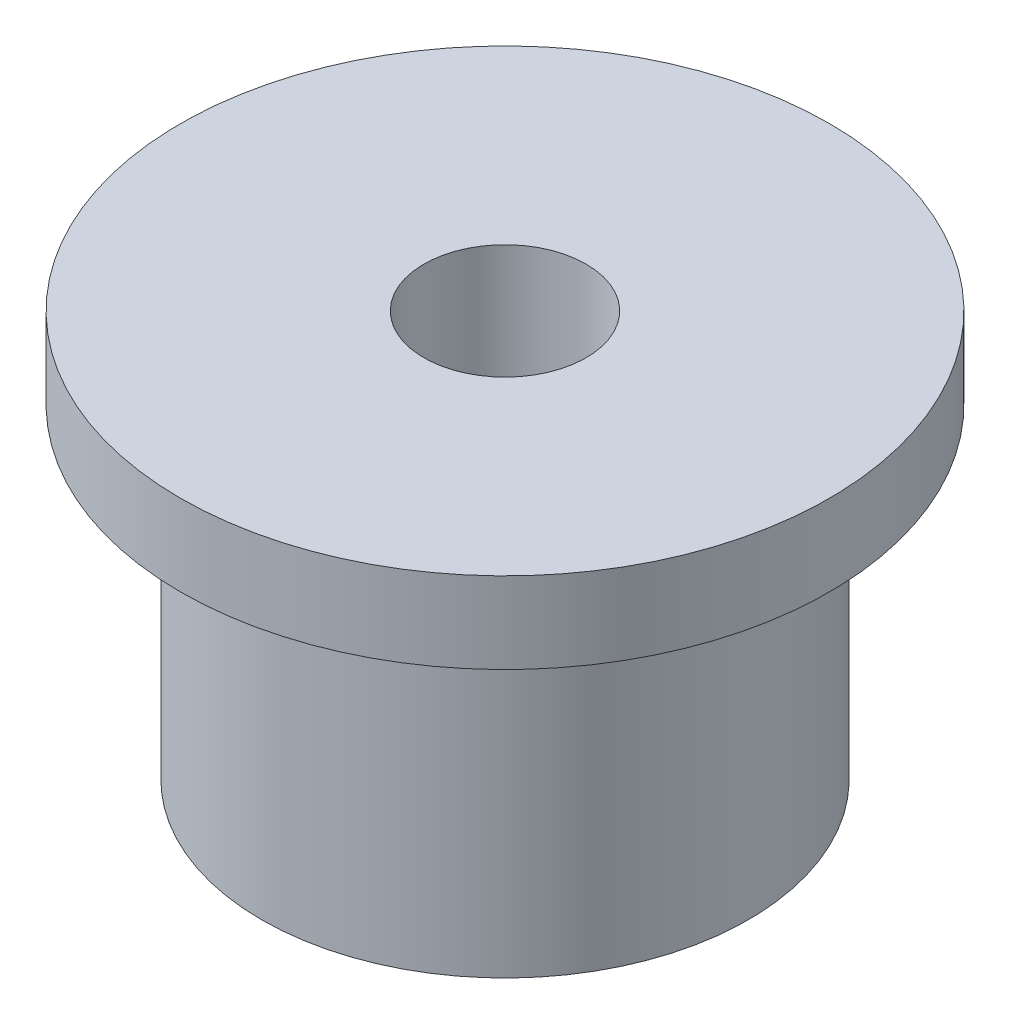
SolidWorks part; units mm, degrees
ref_plane "Front Plane" through (0, 0, 0) normal (0, 0, 1) x (1, 0, 0)
ref_plane "Top Plane" through (0, 0, 0) normal (0, 1, 0) x (1, 0, 0)
ref_plane "Right Plane" through (0, 0, 0) normal (1, 0, 0) x (0, 0, -1)
sketch "Sketch1" plane through (0, 0, 0) normal (0, 1, 0) x (1, 0, 0)
  circle A0 centre (0, 0) radius 100
  dimension "D1" = 200
extrude "Boss-Extrude1" add sketch "Sketch1" along normal blind 25
sketch "Sketch3" plane through (0, 0, 0) normal (0, -1, 0) x (1, 0, 0)
  circle A0 centre (0, 0) radius 75
  dimension "D1" = 150
extrude "Boss-Extrude2" add sketch "Sketch3" along normal blind 100
sketch "Sketch4" plane through (0, -100, 0) normal (0, -1, 0) x (1, 0, 0)
  circle A0 centre (0, 0) radius 25
  dimension "D1" = 50
extrude "Cut-Extrude1" cut sketch "Sketch4" against normal through all
